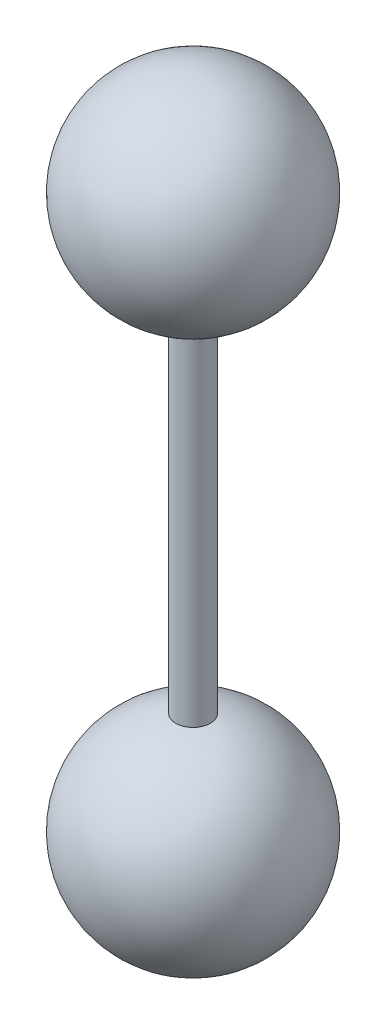
SolidWorks part; units mm, degrees
material "Beech"
ref_plane "Front Plane" through (0, 0, 0) normal (0, 0, 1) x (1, 0, 0)
ref_plane "Top Plane" through (0, 0, 0) normal (0, 1, 0) x (1, 0, 0)
ref_plane "Right Plane" through (0, 0, 0) normal (1, 0, 0) x (0, 0, -1)
sketch "Sketch1" plane through (0, 0, 0) normal (0, 0, 1) x (1, 0, 0)
  line L0 (0, 0) -> (0.25, 0)
  line L1 (0.25, 0) -> (0.25, 2.521)
  line L3 (0, 5.5) -> (0, 0)
  line L4 (0, 0) -> (0, 5.5) construction
  line L5 (0, 4) -> (0, 24.1174) construction
  arc A0 (0.25, 2.521) -> (0, 5.5) centre (0, 4) ccw
  dimension "D2" = 3
  dimension "D3" = 4
  dimension "D1" = 0.5
revolve "Revolve1" add sketch "Sketch1" angle 360 about L3
mirror "Mirror1" about plane through (0, 0, 0) normal (0, 1, 0) of bodies 104
